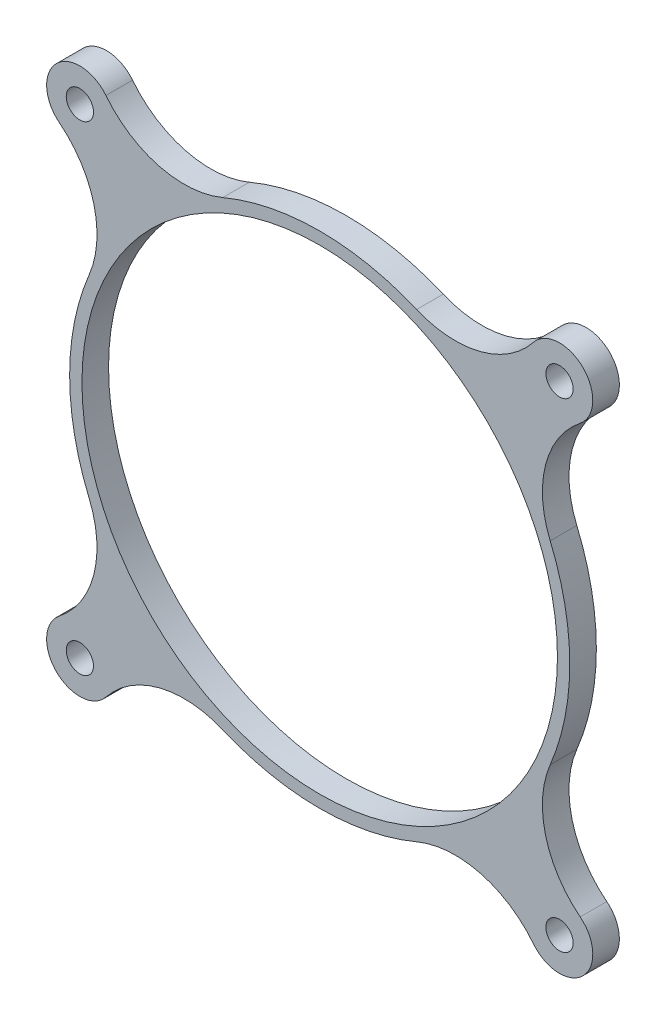
SolidWorks part; units mm, degrees
ref_plane "Front Plane" through (0, 0, 0) normal (1, 0, 0) x (0, 1, 0)
ref_plane "Top Plane" through (0, 0, 0) normal (0, 0, 1) x (0, 1, 0)
ref_plane "Right Plane" through (0, 0, 0) normal (0, 1, 0) x (-1, 0, 0)
sketch "Sketch2" plane through (0, 0, 0) normal (0, 0, 1) x (0, 1, 0)
  line L0 (0, 0) -> (0, 23.0687) construction
  line L1 (0, 0) -> (22.494, 0) construction
  line L2 (0, 0) -> (-63.2005, 63.2005) construction
  circle A0 centre (0, 0) radius 51 construction
  arc A1 (-32.1443, 39.1686) -> (-39.1686, 32.1443) centre (-36.0624, 36.0624) ccw
  arc A2 (32.1443, 39.1686) -> (39.1686, 32.1443) centre (36.0624, 36.0624) cw
  arc A3 (32.1443, -39.1686) -> (39.1686, -32.1443) centre (36.0624, -36.0624) ccw
  arc A4 (-32.1443, -39.1686) -> (-39.1686, -32.1443) centre (-36.0624, -36.0624) cw
  arc A5 (-34.66, 14.5754) -> (-34.66, -14.5754) centre (0, 0) ccw
  arc A6 (-39.1686, 32.1443) -> (-34.66, 14.5754) centre (-48.4872, 20.39) cw
  circle A7 centre (0, 0) radius 34
  arc A8 (-32.1443, 39.1686) -> (-14.5754, 34.66) centre (-20.39, 48.4872) ccw
  circle A9 centre (-36.0624, 36.0624) radius 2.05
  arc A10 (32.1443, 39.1686) -> (14.5754, 34.66) centre (20.39, 48.4872) cw
  arc A11 (39.1686, 32.1443) -> (34.66, 14.5754) centre (48.4872, 20.39) ccw
  circle A12 centre (36.0624, 36.0624) radius 2.05
  arc A13 (32.1443, -39.1686) -> (14.5754, -34.66) centre (20.39, -48.4872) ccw
  arc A14 (39.1686, -32.1443) -> (34.66, -14.5754) centre (48.4872, -20.39) cw
  circle A15 centre (36.0624, -36.0624) radius 2.05
  circle A16 centre (-36.0624, -36.0624) radius 2.05
  arc A17 (-32.1443, -39.1686) -> (-14.5754, -34.66) centre (-20.39, -48.4872) cw
  arc A18 (-39.1686, -32.1443) -> (-34.66, -14.5754) centre (-48.4872, -20.39) ccw
  arc A19 (-14.5754, -34.66) -> (14.5754, -34.66) centre (0, 0) ccw
  arc A20 (34.66, -14.5754) -> (34.66, 14.5754) centre (0, 0) ccw
  arc A21 (14.5754, 34.66) -> (-14.5754, 34.66) centre (0, 0) ccw
  dimension "D1" = 102
  dimension "D3" = 10
  dimension "D4" = 75.2
  dimension "D5" = 68
  dimension "D6" = 15
  dimension "D7" = 4.1
  dimension "D2" = 45
extrude "Boss-Extrude1" add sketch "Sketch2" along normal blind 4
sketch "Sketch3" plane through (0, 0, 0) normal (0, 0, 1) x (0, 1, 0)
  circle A2 centre (0, 0) radius 34
  circle A3 centre (0, 0) radius 35.75
  dimension "D1" = 68
  dimension "D2" = 71.5
extrude "Cut-Extrude1" cut sketch "Sketch3" against normal blind 10 from surface at 4 starting at face at (0, 0, 4)
